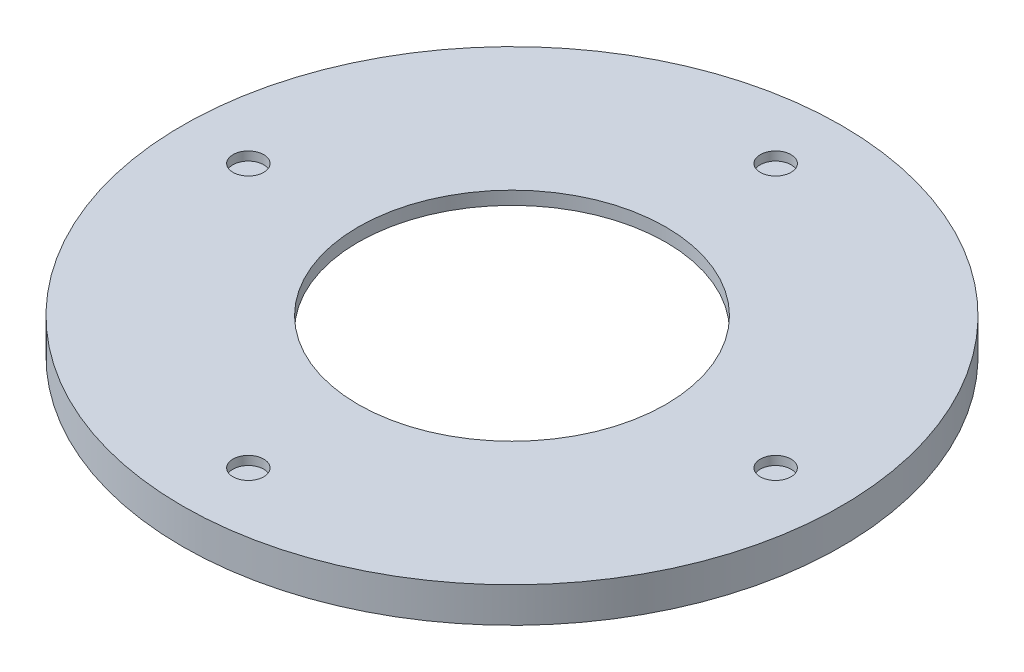
SolidWorks part; units mm, degrees
ref_plane "Front Plane" through (0, 0, 0) normal (0, 0, 1) x (1, 0, 0)
ref_plane "Top Plane" through (0, 0, 0) normal (0, 1, 0) x (1, 0, 0)
ref_plane "Right Plane" through (0, 0, 0) normal (1, 0, 0) x (0, 0, -1)
sketch "Sketch1" plane through (0, 0, 0) normal (0, 1, 0) x (1, 0, 0)
  circle A0 centre (0, 0) radius 37.5
  dimension "D1" = 75
extrude "Boss-Extrude1" add sketch "Sketch1" along normal blind 4
sketch "Sketch2" plane through (0, 4, 0) normal (0, 1, 0) x (1, 0, 0)
  line L0 (0, -30) -> (0, 30) construction
  line L1 (30, 0) -> (-30, 0) construction
  circle A0 centre (0, 0) radius 30 construction
  circle A2 centre (0, 30) radius 1.75
  circle A3 centre (30, 0) radius 1.75
  circle A4 centre (0, -30) radius 1.75
  circle A5 centre (-30, 0) radius 1.75
  dimension "D1" = 60
  dimension "D2" = 3.5
  dimension "D3" = 60
extrude "Cut-Extrude1" cut sketch "Sketch2" against normal blind 1
sketch "Sketch3" plane through (0, 0, 0) normal (0, -1, 0) x (-1, 0, 0)
  circle A0 centre (0, 0) radius 35
  dimension "D1" = 70
extrude "Cut-Extrude5" cut sketch "Sketch3" against normal blind 2.5
sketch "Sketch4" plane through (0, 2.5, 0) normal (0, -1, 0) x (-1, 0, 0)
  circle A0 centre (0, 0) radius 17.5
  dimension "D1" = 35
extrude "Cut-Extrude6" cut sketch "Sketch4" against normal through all
